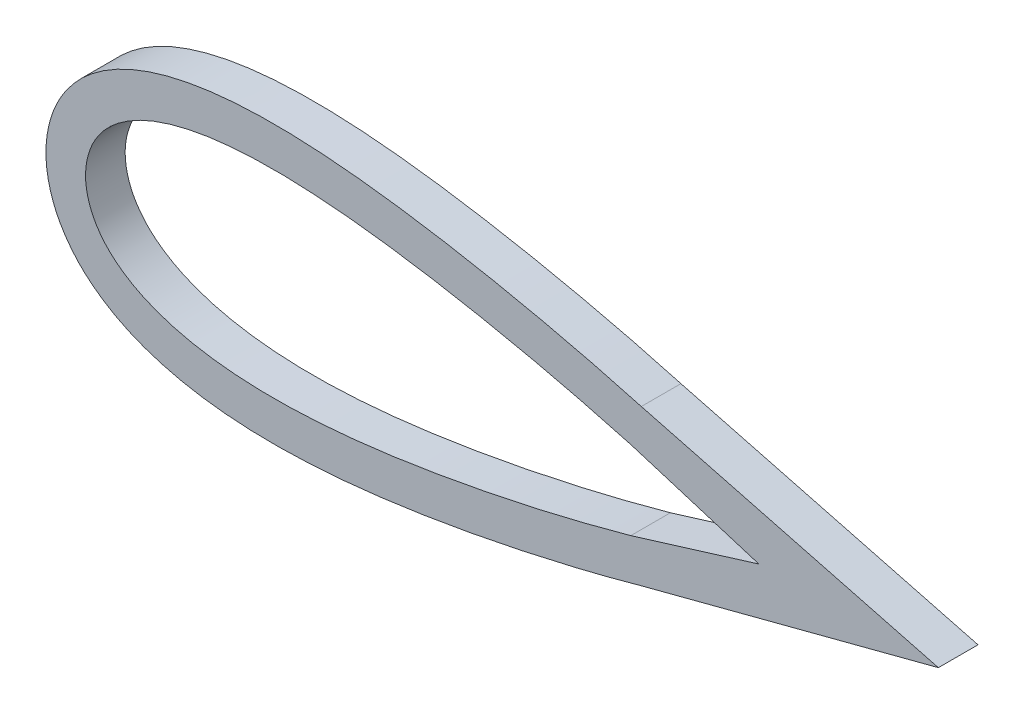
SolidWorks part; units mm, degrees
ref_plane "Front Plane" through (0, 0, 0) normal (0, 0, 1) x (1, 0, 0)
ref_plane "Top Plane" through (0, 0, 0) normal (0, 1, 0) x (1, 0, 0)
ref_plane "Right Plane" through (0, 0, 0) normal (1, 0, 0) x (0, 0, -1)
curve "Curve1"
  spline degree 3 poles (25, 0.0632, 0) (24.5837, 0.1778, 0) (23.7526, 0.4066, 0) (22.0881, 0.8323, 0) (20.0071, 1.3211, 0) (17.5066, 1.8422, 0) (15.0067, 2.2943, 0) (12.5068, 2.6638, 0) (10.0058, 2.9265, 0) (7.9173, 3.0191, 0) (6.2482, 2.9827, 0) (4.9946, 2.8834, 0) (3.7369, 2.6921, 0) (2.6917, 2.4234, 0) (1.8599, 2.1065, 0) (1.218, 1.781, 0) (0.6841, 1.3923, 0) (0.1811, 0.8309, 0) (-0.1225, 0, 0) (0.1811, -0.8309, 0) (0.6841, -1.3923, 0) (1.218, -1.781, 0) (1.8599, -2.1065, 0) (2.6917, -2.4234, 0) (3.7369, -2.6921, 0) (4.9946, -2.8834, 0) (6.2482, -2.9827, 0) (7.9173, -3.0191, 0) (10.0058, -2.9265, 0) (12.5068, -2.6638, 0) (15.0067, -2.2943, 0) (17.5066, -1.8422, 0) (20.0071, -1.3211, 0) (22.0881, -0.8323, 0) (23.7526, -0.4066, 0) (24.5837, -0.1778, 0) (25, -0.0632, 0) knots 0 0 0 0 0.024459 0.048825 0.097314 0.145528 0.193488 0.241191 0.288638 0.335878 0.359486 0.383166 0.407055 0.431473 0.444122 0.457403 0.472168 0.481175 0.5 0.518825 0.527832 0.542597 0.555878 0.568527 0.592945 0.616834 0.640514 0.664122 0.711362 0.758809 0.806512 0.854472 0.902686 0.951175 0.975541 1 1 1 1
sketch "Sketch2" plane through (0, 0, 0) normal (0, 0, 1) x (1, 0, 0)
  line L0 (3.9941, 0) -> (45.7263, 0) construction
  line L1 (26.0616, 3.9198) -> (41.0616, 0)
  line L2 (41.0616, 0) -> (26.0616, -3.9198)
  line L3 (25.5308, 1.9915) -> (32, 0)
  line L4 (32, 0) -> (25.5308, -1.9915)
  spline S3 degree 3 poles (25.5308, 1.9915) (24.4463, 2.29) (22.2703, 2.8612) (18.9743, 3.5945) (15.6526, 4.2237) (12.8457, 4.6388) (10.5613, 4.8744) (8.8232, 4.9872) (7.0594, 5.0165) (5.2549, 4.9317) (3.7193, 4.7271) (2.4529, 4.432) (1.4907, 4.1229) (0.4966, 3.6849) (-0.3641, 3.1287) (-1.0379, 2.4976) (-1.5495, 1.7991) (-1.8969, 0.9885) (-2.0516, 0) (-1.8969, -0.9885) (-1.5495, -1.7991) (-1.0379, -2.4976) (-0.3641, -3.1287) (0.4966, -3.6849) (1.4907, -4.1229) (2.4529, -4.432) (3.7193, -4.7271) (5.2549, -4.9317) (7.0594, -5.0165) (8.8232, -4.9872) (10.5613, -4.8744) (12.8457, -4.6388) (15.6526, -4.2237) (18.9743, -3.5945) (22.2703, -2.8612) (24.4463, -2.29) (25.5308, -1.9915) knots 0 0 0 0 0.0625 0.125 0.1875 0.25 0.28125 0.3125 0.34375 0.375 0.40625 0.421875 0.4375 0.453125 0.46875 0.476562 0.484375 0.492188 0.5 0.507812 0.515625 0.523438 0.53125 0.546875 0.5625 0.578125 0.59375 0.625 0.65625 0.6875 0.71875 0.75 0.8125 0.875 0.9375 1 1 1 1
  spline S5 degree 3 poles (26.0616, 3.9198) (25.7909, 3.9943) (25.2572, 4.1414) (24.1247, 4.4432) (22.1788, 4.9278) (19.3791, 5.5544) (15.9884, 6.1955) (13.1047, 6.6227) (10.7315, 6.8676) (8.9078, 6.9861) (7.036, 7.0178) (5.0815, 6.9264) (3.3793, 6.7015) (1.9226, 6.3627) (0.7872, 5.9988) (-0.444, 5.4594) (-1.5825, 4.7282) (-2.5302, 3.8456) (-3.3073, 2.7916) (-3.7478, 1.7539) (-3.9591, 0.7984) (-4.0205, 0) (-3.9591, -0.7984) (-3.7478, -1.7539) (-3.3073, -2.7916) (-2.5302, -3.8456) (-1.5825, -4.7282) (-0.444, -5.4594) (0.7872, -5.9988) (1.9226, -6.3627) (3.3793, -6.7015) (5.0815, -6.9264) (7.036, -7.0178) (8.9078, -6.9861) (10.7315, -6.8676) (13.1047, -6.6227) (15.9884, -6.1955) (19.3791, -5.5544) (22.1788, -4.9278) (24.1247, -4.4432) (25.2572, -4.1414) (25.7909, -3.9943) (26.0616, -3.9198) knots 0 0 0 0 0.015625 0.03125 0.0625 0.125 0.1875 0.25 0.28125 0.3125 0.34375 0.375 0.40625 0.421875 0.4375 0.453125 0.46875 0.476562 0.484375 0.492188 0.496094 0.5 0.503906 0.507812 0.515625 0.523438 0.53125 0.546875 0.5625 0.578125 0.59375 0.625 0.65625 0.6875 0.71875 0.75 0.8125 0.875 0.9375 0.96875 0.984375 1 1 1 1
  dimension "D3" = 15
  dimension "D4" = 32
extrude "Boss-Extrude1" add sketch "Sketch2" along normal blind 2
